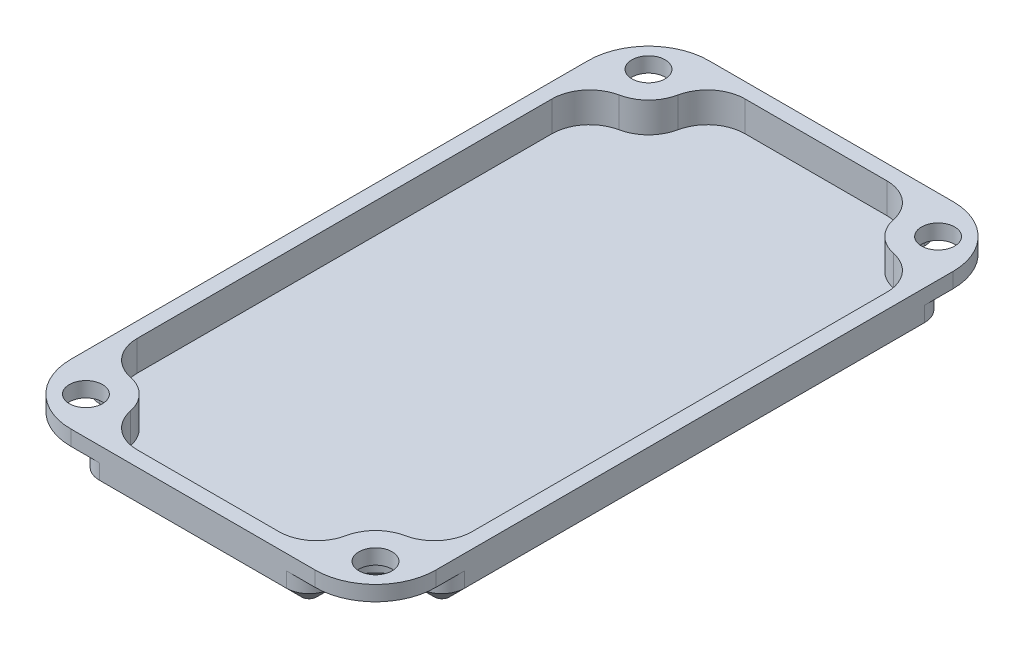
SolidWorks part; units mm, degrees
ref_plane "前视基准面" through (0, 0, 0) normal (0, 0, 1) x (1, 0, 0)
ref_plane "上视基准面" through (0, 0, 0) normal (0, 1, 0) x (1, 0, 0)
ref_plane "右视基准面" through (0, 0, 0) normal (1, 0, 0) x (0, 0, -1)
other "Configuration Table"
sketch "草图1" plane through (0, 0, 0) normal (0, 1, 0) x (1, 0, 0)
  line L1 (-12.1, -21.15) -> (12.1, -21.15)
  line L2 (-12.1, -21.15) -> (-12.1, 21.15)
  line L3 (-12.1, 21.15) -> (12.1, 21.15)
  line L4 (12.1, -21.15) -> (12.1, 21.15)
  line L5 (0, 21.15) -> (0, -21.15) construction
  line L6 (-12.1, 0) -> (12.1, 0) construction
  point P0 (0, 0)
  dimension "D1" = 24.2
  dimension "D2" = 42.3
extrude "凸台-拉伸1" add sketch "草图1" along normal blind 3
fillet "圆角1" radius 4 4 edges at (-12.1, 1.5, -21.15) (12.1, 1.5, -21.15) (-12.1, 1.5, 21.15) (12.1, 1.5, 21.15)
sketch "草图2" plane through (0, 3, 0) normal (0, 1, 0) x (1, 0, 0)
  line L8 (8.1, 20.15) -> (-8.1, 20.15)
  line L9 (-11.1, 17.15) -> (-11.1, -17.15)
  line L10 (-8.1, -20.15) -> (8.1, -20.15)
  line L11 (11.1, -17.15) -> (11.1, 17.15)
  line L12 (8.1, 20.15) -> (-8.1, 20.15)
  line L13 (-11.1, 17.15) -> (-11.1, -17.15)
  line L14 (-8.1, -20.15) -> (8.1, -20.15)
  line L15 (11.1, -17.15) -> (11.1, 17.15)
  arc A8 (-8.1, 20.15) -> (-11.1, 17.15) centre (-8.1, 17.15) ccw
  arc A9 (-11.1, -17.15) -> (-8.1, -20.15) centre (-8.1, -17.15) ccw
  arc A10 (8.1, -20.15) -> (11.1, -17.15) centre (8.1, -17.15) ccw
  arc A11 (11.1, 17.15) -> (8.1, 20.15) centre (8.1, 17.15) ccw
  arc A12 (-8.1, 20.15) -> (-11.1, 17.15) centre (-8.1, 17.15) ccw
  arc A13 (-11.1, -17.15) -> (-8.1, -20.15) centre (-8.1, -17.15) ccw
  arc A14 (8.1, -20.15) -> (11.1, -17.15) centre (8.1, -17.15) ccw
  arc A15 (11.1, 17.15) -> (8.1, 20.15) centre (8.1, 17.15) ccw
  dimension "D1" = 1
extrude "切除-拉伸1" cut sketch "草图2" against normal offset from surface (2 mm away) 1 up to face at (0, 0, 0)
sketch "草图3" plane through (0, 1, 0) normal (0, 1, 0) x (1, 0, 0)
  line L0 (-12.1, 17.15) -> (-12.1, -17.15) construction
  line L1 (-9.6, -18.65) -> (9.6, -18.65) construction
  line L2 (-9.6, -18.65) -> (-9.6, 18.65) construction
  line L3 (-9.6, 18.65) -> (9.6, 18.65) construction
  line L4 (9.6, -18.65) -> (9.6, 18.65) construction
  line L5 (0, 18.65) -> (0, -18.65) construction
  line L6 (-9.6, 0) -> (9.6, 0) construction
  line L7 (8.1, 21.15) -> (-8.1, 21.15) construction
  line L12 (-9.6, 16.15) -> (-11.1, 16.15)
  line L13 (-7.1, 18.65) -> (-7.1, 20.15)
  line L14 (7.1, 18.65) -> (7.1, 20.15)
  line L15 (9.6, 16.15) -> (11.1, 16.15)
  line L16 (8.1, 20.15) -> (-8.1, 20.15)
  line L17 (-11.1, 17.15) -> (-11.1, -17.15)
  line L18 (-8.1, -20.15) -> (8.1, -20.15)
  line L19 (11.1, -17.15) -> (11.1, 17.15)
  line L20 (8.1, 20.15) -> (7.1, 20.15)
  line L21 (-11.1, 17.15) -> (-11.1, 16.15)
  line L22 (-8.1, -20.15) -> (-7.1, -20.15)
  line L23 (11.1, -17.15) -> (11.1, -16.15)
  line L24 (7.1, -18.65) -> (7.1, -20.15)
  line L25 (9.6, -16.15) -> (11.1, -16.15)
  line L26 (-9.6, -16.15) -> (-11.1, -16.15)
  line L27 (-7.1, -18.65) -> (-7.1, -20.15)
  line L28 (7.1, 20.15) -> (-7.1, 20.15) construction
  line L29 (-7.1, 20.15) -> (-8.1, 20.15)
  line L30 (-11.1, 16.15) -> (-11.1, -16.15) construction
  line L31 (-11.1, -16.15) -> (-11.1, -17.15)
  line L32 (11.1, -16.15) -> (11.1, 16.15) construction
  line L33 (11.1, 16.15) -> (11.1, 17.15)
  line L34 (-7.1, -20.15) -> (7.1, -20.15) construction
  line L35 (7.1, -20.15) -> (8.1, -20.15)
  arc A0 (-9.6, 16.15) -> (-7.1, 18.65) centre (-9.6, 18.65) ccw
  arc A1 (7.1, 18.65) -> (9.6, 16.15) centre (9.6, 18.65) ccw
  arc A2 (-7.1, -18.65) -> (-9.6, -16.15) centre (-9.6, -18.65) ccw
  arc A3 (9.6, -16.15) -> (7.1, -18.65) centre (9.6, -18.65) ccw
  arc A8 (-7.5648, 20.1019) -> (-11.0519, 16.6148) centre (-9.6, 18.65) ccw construction
  arc A9 (-11.0519, 16.6148) -> (-9.6, 16.15) centre (-9.6, 18.65) ccw construction
  arc A10 (-7.1, 18.65) -> (-7.5648, 20.1019) centre (-9.6, 18.65) ccw construction
  arc A11 (7.5648, -20.1019) -> (11.0519, -16.6148) centre (9.6, -18.65) ccw construction
  arc A12 (11.1, 17.15) -> (8.1, 20.15) centre (8.1, 17.15) ccw
  arc A13 (-8.1, 20.15) -> (-11.1, 17.15) centre (-8.1, 17.15) ccw
  arc A14 (-11.1, -17.15) -> (-8.1, -20.15) centre (-8.1, -17.15) ccw
  arc A15 (8.1, -20.15) -> (11.1, -17.15) centre (8.1, -17.15) ccw
  arc A16 (11.1, 17.15) -> (8.1, 20.15) centre (8.1, 17.15) ccw
  arc A17 (-8.1, 20.15) -> (-11.1, 17.15) centre (-8.1, 17.15) ccw
  arc A18 (-11.1, -17.15) -> (-8.1, -20.15) centre (-8.1, -17.15) ccw
  arc A19 (8.1, -20.15) -> (11.1, -17.15) centre (8.1, -17.15) ccw
  arc A20 (7.1, -18.65) -> (7.5648, -20.1019) centre (9.6, -18.65) ccw construction
  arc A21 (11.0519, -16.6148) -> (9.6, -16.15) centre (9.6, -18.65) ccw construction
  arc A22 (-11.0519, -16.6148) -> (-7.5648, -20.1019) centre (-9.6, -18.65) ccw construction
  arc A23 (-9.6, -16.15) -> (-11.0519, -16.6148) centre (-9.6, -18.65) ccw construction
  arc A24 (-7.5648, -20.1019) -> (-7.1, -18.65) centre (-9.6, -18.65) ccw construction
  arc A25 (11.0519, 16.6148) -> (7.5648, 20.1019) centre (9.6, 18.65) ccw construction
  arc A26 (7.5648, 20.1019) -> (7.1, 18.65) centre (9.6, 18.65) ccw construction
  arc A27 (9.6, 16.15) -> (11.0519, 16.6148) centre (9.6, 18.65) ccw construction
  point P8 (0, 0)
  dimension "D3" = 5
  dimension "D1" = 2.5
  dimension "D2" = 2.5
  dimension "D4" = 0
extrude "凸台-拉伸2" add sketch "草图3" along normal up to surface (2 mm away) up to face at (0, 3, 0)
fillet "圆角2" radius 2.5 8 edges at (7.1, 2, 20.15) (11.1, 2, 16.15) (11.1, 2, -16.15) (7.1, 2, -20.15) (-7.1, 2, -20.15) (-11.1, 2, 16.15) (-7.1, 2, 20.15) (-11.1, 2, -16.15)
sketch "草图4" plane through (0, 0, 0) normal (0, -1, 0) x (1, 0, 0)
  line L0 (-8.1, 21.15) -> (8.1, 21.15) construction
  line L1 (-9.6, -18.65) -> (9.6, -18.65) construction
  line L2 (-9.6, -18.65) -> (-9.6, 18.65) construction
  line L3 (-9.6, 18.65) -> (9.6, 18.65) construction
  line L4 (9.6, -18.65) -> (9.6, 18.65) construction
  line L5 (0, 18.65) -> (0, -18.65) construction
  line L6 (-9.6, 0) -> (9.6, 0) construction
  line L7 (-12.1, -17.15) -> (-12.1, 17.15) construction
  circle A0 centre (-9.6, 18.65) radius 1.1
  circle A1 centre (9.6, 18.65) radius 1.1
  circle A2 centre (9.6, -18.65) radius 1.1
  circle A3 centre (-9.6, -18.65) radius 1.1
  point P0 (0, 0)
  dimension "D1" = 2.2
  dimension "D2" = 2.5
  dimension "D3" = 2.5
extrude "切除-拉伸2" cut sketch "草图4" against normal through all and the other way through all
sketch "草图5" plane through (0, 0, 0) normal (0, -1, 0) x (1, 0, 0)
  line L0 (-12.1, -17.15) -> (-12.1, 17.15) construction
  line L1 (-9.6, 16.75) -> (-12.1, 16.75)
  line L2 (-7.7, 18.65) -> (-7.7, 21.15)
  line L3 (-7.7, 21.15) -> (-12.1, 21.15)
  line L4 (-12.1, 16.75) -> (-12.1, 21.15)
  line L5 (9.6, 16.75) -> (12.1, 16.75)
  line L6 (7.7, 18.65) -> (7.7, 21.15)
  line L7 (7.7, 21.15) -> (12.1, 21.15)
  line L8 (12.1, 16.75) -> (12.1, 21.15)
  line L9 (9.6, -16.75) -> (12.1, -16.75)
  line L10 (7.7, -18.65) -> (7.7, -21.15)
  line L11 (7.7, -21.15) -> (12.1, -21.15)
  line L12 (12.1, -16.75) -> (12.1, -21.15)
  line L13 (-9.6, -16.75) -> (-12.1, -16.75)
  line L14 (-7.7, -18.65) -> (-7.7, -21.15)
  line L15 (-7.7, -21.15) -> (-12.1, -21.15)
  line L16 (-12.1, -16.75) -> (-12.1, -21.15)
  line L17 (-7.7, 16.75) -> (-7.7, 18.65) construction
  line L18 (-7.7, 16.75) -> (-9.6, 16.75) construction
  line L19 (7.7, 16.75) -> (9.6, 16.75) construction
  line L20 (7.7, 16.75) -> (7.7, 18.65) construction
  line L21 (7.7, -16.75) -> (9.6, -16.75) construction
  line L22 (7.7, -16.75) -> (7.7, -18.65) construction
  line L23 (-7.7, -16.75) -> (-9.6, -16.75) construction
  line L24 (-7.7, -16.75) -> (-7.7, -18.65) construction
  line L25 (-8.1, 21.15) -> (8.1, 21.15) construction
  line L26 (8.1, -21.15) -> (-8.1, -21.15) construction
  arc A24 (-9.6, 16.75) -> (-7.7, 18.65) centre (-9.6, 18.65) ccw
  arc A25 (7.7, 18.65) -> (9.6, 16.75) centre (9.6, 18.65) ccw
  arc A26 (-7.7, -18.65) -> (-9.6, -16.75) centre (-9.6, -18.65) ccw
  arc A27 (9.6, -16.75) -> (7.7, -18.65) centre (9.6, -18.65) ccw
  arc A28 (-9.6, -16.75) -> (-7.7, -18.65) centre (-9.6, -18.65) ccw construction
  arc A29 (7.7, -18.65) -> (9.6, -16.75) centre (9.6, -18.65) ccw construction
  arc A30 (9.6, 16.75) -> (7.7, 18.65) centre (9.6, 18.65) ccw construction
  arc A31 (-7.7, 18.65) -> (-9.6, 16.75) centre (-9.6, 18.65) ccw construction
  point P1 (-13.4823, 16.75)
  point P3 (-12.1, 16.75)
  point P5 (7.7, 21.15)
  point P22 (-12.1, -16.75)
  point P35 (0, 0)
  point P36 (7.7, -21.15)
  dimension "D1" = 3.8
extrude "切除-拉伸3" cut sketch "草图5" against normal blind 2
fillet "圆角3" radius 1.5 8 edges at (-12.1, 1, -16.75) (-7.7, 1, 21.15) (7.7, 1, 21.15) (12.1, 1, 16.75) (12.1, 1, -16.75) (7.7, 1, -21.15) (-7.7, 1, -21.15) (-12.1, 1, 16.75)
chamfer "倒角1" distance 1 angle 45 24 edges at (12.1, 0, 0) (11.6607, 0, -16.3107) (11.6607, 0, 16.3107) (10.1, 0, -16.75) (10.1, 0, 16.75) (8.2565, 0, -17.3065) (8.2565, 0, 17.3065) (7.7, 0, -19.15) (7.7, 0, 19.15) (7.2607, 0, -20.7107) (7.2607, 0, 20.7107) (0, 0, -21.15) (0, 0, 21.15) (-7.2607, 0, -20.7107) (-7.2607, 0, 20.7107) (-7.7, 0, -19.15) (-7.7, 0, 19.15) (-8.2565, 0, -17.3065) (-8.2565, 0, 17.3065) (-10.1, 0, -16.75) (-10.1, 0, 16.75) (-11.6607, 0, -16.3107) (-11.6607, 0, 16.3107) (-12.1, 0, 0)
